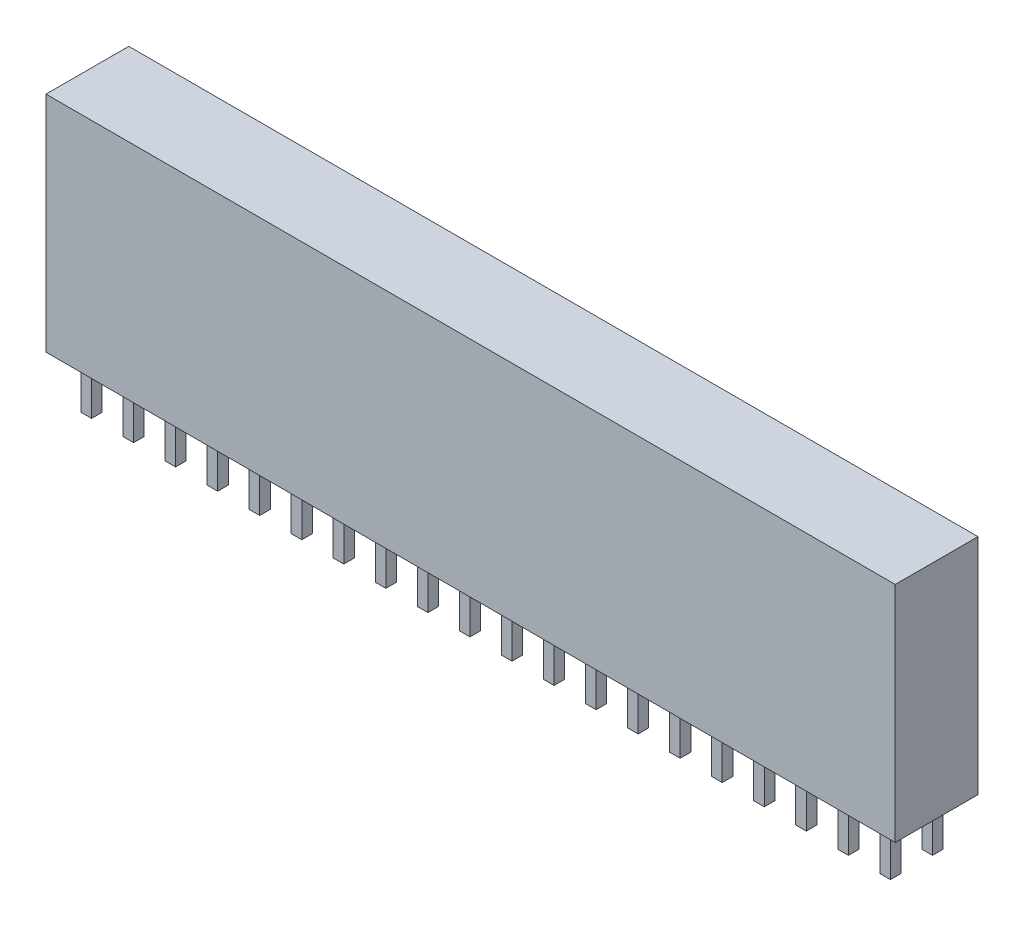
SolidWorks part; units mm, degrees
ref_plane "Front Plane" through (0, 0, 0) normal (0, 0, 1) x (1, 0, 0)
ref_plane "Top Plane" through (0, 0, 0) normal (0, 1, 0) x (1, 0, 0)
ref_plane "Right Plane" through (0, 0, 0) normal (1, 0, 0) x (0, 0, -1)
sketch "Sketch1" plane through (0, 0, 0) normal (0, 1, 0) x (1, 0, 0)
  line L1 (-25.65, -2.5) -> (25.65, -2.5)
  line L2 (-25.65, -2.5) -> (-25.65, 2.5)
  line L3 (-25.65, 2.5) -> (25.65, 2.5)
  line L4 (25.65, -2.5) -> (25.65, 2.5)
  line L5 (-25.65, -2.5) -> (25.65, 2.5) construction
  line L6 (-25.65, 2.5) -> (25.65, -2.5) construction
  point P0 (0, 0)
  dimension "D1" = 5
  dimension "D2" = 51.3
extrude "Boss-Extrude1" add sketch "Sketch1" along normal blind 13.5
sketch "Sketch2" plane through (0, 0, 0) normal (0, -1, 0) x (1, 0, 0)
  line L0 (-25.65, 0) -> (25.65, 0) construction
  line L1 (-25.65, -2.5) -> (-25.65, 2.5) construction
  line L2 (25.65, 2.5) -> (25.65, -2.5) construction
  line L3 (-25.65, 1.27) -> (25.65, 1.27) construction
  line L4 (-25.65, -1.27) -> (25.65, -1.27) construction
  line L5 (0, -2.5) -> (0, 2.5) construction
  line L6 (25.65, -2.5) -> (-25.65, -2.5) construction
  line L7 (-25.65, 2.5) -> (25.65, 2.5) construction
  line L8 (-21.91, 1.59) -> (-21.27, 1.59)
  line L9 (-24.45, 0.95) -> (-23.81, 0.95)
  line L10 (-24.45, 0.95) -> (-24.45, 1.59)
  line L11 (-24.45, 1.59) -> (-23.81, 1.59)
  line L12 (-23.81, 0.95) -> (-23.81, 1.59)
  line L13 (-24.45, 0.95) -> (-23.81, 1.59) construction
  line L14 (-24.45, 1.59) -> (-23.81, 0.95) construction
  line L15 (-21.91, 0.95) -> (-21.91, 1.59)
  line L16 (-21.91, 0.95) -> (-21.27, 0.95)
  line L17 (-21.27, 0.95) -> (-21.27, 1.59)
  line L18 (-19.37, 1.59) -> (-18.73, 1.59)
  line L19 (-19.37, 0.95) -> (-19.37, 1.59)
  line L20 (-19.37, 0.95) -> (-18.73, 0.95)
  line L21 (-18.73, 0.95) -> (-18.73, 1.59)
  line L22 (-16.83, 1.59) -> (-16.19, 1.59)
  line L23 (-16.83, 0.95) -> (-16.83, 1.59)
  line L24 (-16.83, 0.95) -> (-16.19, 0.95)
  line L25 (-16.19, 0.95) -> (-16.19, 1.59)
  line L26 (-14.29, 1.59) -> (-13.65, 1.59)
  line L27 (-14.29, 0.95) -> (-14.29, 1.59)
  line L28 (-14.29, 0.95) -> (-13.65, 0.95)
  line L29 (-13.65, 0.95) -> (-13.65, 1.59)
  line L30 (-11.75, 1.59) -> (-11.11, 1.59)
  line L31 (-11.75, 0.95) -> (-11.75, 1.59)
  line L32 (-11.75, 0.95) -> (-11.11, 0.95)
  line L33 (-11.11, 0.95) -> (-11.11, 1.59)
  line L34 (-9.21, 1.59) -> (-8.57, 1.59)
  line L35 (-9.21, 0.95) -> (-9.21, 1.59)
  line L36 (-9.21, 0.95) -> (-8.57, 0.95)
  line L37 (-8.57, 0.95) -> (-8.57, 1.59)
  line L38 (-6.67, 1.59) -> (-6.03, 1.59)
  line L39 (-6.67, 0.95) -> (-6.67, 1.59)
  line L40 (-6.67, 0.95) -> (-6.03, 0.95)
  line L41 (-6.03, 0.95) -> (-6.03, 1.59)
  line L42 (-4.13, 1.59) -> (-3.49, 1.59)
  line L43 (-4.13, 0.95) -> (-4.13, 1.59)
  line L44 (-4.13, 0.95) -> (-3.49, 0.95)
  line L45 (-3.49, 0.95) -> (-3.49, 1.59)
  line L46 (-1.59, 1.59) -> (-0.95, 1.59)
  line L47 (-1.59, 0.95) -> (-1.59, 1.59)
  line L48 (-1.59, 0.95) -> (-0.95, 0.95)
  line L49 (-0.95, 0.95) -> (-0.95, 1.59)
  line L50 (24.45, 0.95) -> (24.45, 1.59)
  line L51 (23.81, 0.95) -> (23.81, 1.59)
  line L52 (24.45, 1.59) -> (23.81, 1.59)
  line L53 (24.45, 0.95) -> (23.81, 0.95)
  line L54 (0.95, 0.95) -> (0.95, 1.59)
  line L55 (1.59, 0.95) -> (0.95, 0.95)
  line L56 (1.59, 0.95) -> (1.59, 1.59)
  line L57 (1.59, 1.59) -> (0.95, 1.59)
  line L58 (3.49, 0.95) -> (3.49, 1.59)
  line L59 (4.13, 0.95) -> (3.49, 0.95)
  line L60 (4.13, 0.95) -> (4.13, 1.59)
  line L61 (4.13, 1.59) -> (3.49, 1.59)
  line L62 (6.03, 0.95) -> (6.03, 1.59)
  line L63 (6.67, 0.95) -> (6.03, 0.95)
  line L64 (6.67, 0.95) -> (6.67, 1.59)
  line L65 (6.67, 1.59) -> (6.03, 1.59)
  line L66 (8.57, 0.95) -> (8.57, 1.59)
  line L67 (9.21, 0.95) -> (8.57, 0.95)
  line L68 (9.21, 0.95) -> (9.21, 1.59)
  line L69 (9.21, 1.59) -> (8.57, 1.59)
  line L70 (11.11, 0.95) -> (11.11, 1.59)
  line L71 (11.75, 0.95) -> (11.11, 0.95)
  line L72 (11.75, 0.95) -> (11.75, 1.59)
  line L73 (11.75, 1.59) -> (11.11, 1.59)
  line L74 (13.65, 0.95) -> (13.65, 1.59)
  line L75 (14.29, 0.95) -> (13.65, 0.95)
  line L76 (14.29, 0.95) -> (14.29, 1.59)
  line L77 (14.29, 1.59) -> (13.65, 1.59)
  line L78 (16.19, 0.95) -> (16.19, 1.59)
  line L79 (16.83, 0.95) -> (16.19, 0.95)
  line L80 (16.83, 0.95) -> (16.83, 1.59)
  line L81 (16.83, 1.59) -> (16.19, 1.59)
  line L82 (18.73, 0.95) -> (18.73, 1.59)
  line L83 (19.37, 0.95) -> (18.73, 0.95)
  line L84 (19.37, 0.95) -> (19.37, 1.59)
  line L85 (19.37, 1.59) -> (18.73, 1.59)
  line L86 (21.27, 0.95) -> (21.27, 1.59)
  line L87 (21.91, 0.95) -> (21.27, 0.95)
  line L88 (21.91, 0.95) -> (21.91, 1.59)
  line L89 (21.91, 1.59) -> (21.27, 1.59)
  line L90 (21.91, -1.59) -> (21.27, -1.59)
  line L91 (21.91, -0.95) -> (21.91, -1.59)
  line L92 (21.91, -0.95) -> (21.27, -0.95)
  line L93 (21.27, -0.95) -> (21.27, -1.59)
  line L94 (19.37, -1.59) -> (18.73, -1.59)
  line L95 (19.37, -0.95) -> (19.37, -1.59)
  line L96 (19.37, -0.95) -> (18.73, -0.95)
  line L97 (18.73, -0.95) -> (18.73, -1.59)
  line L98 (16.83, -1.59) -> (16.19, -1.59)
  line L99 (16.83, -0.95) -> (16.83, -1.59)
  line L100 (16.83, -0.95) -> (16.19, -0.95)
  line L101 (16.19, -0.95) -> (16.19, -1.59)
  line L102 (14.29, -1.59) -> (13.65, -1.59)
  line L103 (14.29, -0.95) -> (14.29, -1.59)
  line L104 (14.29, -0.95) -> (13.65, -0.95)
  line L105 (13.65, -0.95) -> (13.65, -1.59)
  line L106 (11.75, -1.59) -> (11.11, -1.59)
  line L107 (11.75, -0.95) -> (11.75, -1.59)
  line L108 (11.75, -0.95) -> (11.11, -0.95)
  line L109 (11.11, -0.95) -> (11.11, -1.59)
  line L110 (9.21, -1.59) -> (8.57, -1.59)
  line L111 (9.21, -0.95) -> (9.21, -1.59)
  line L112 (9.21, -0.95) -> (8.57, -0.95)
  line L113 (8.57, -0.95) -> (8.57, -1.59)
  line L114 (6.67, -1.59) -> (6.03, -1.59)
  line L115 (6.67, -0.95) -> (6.67, -1.59)
  line L116 (6.67, -0.95) -> (6.03, -0.95)
  line L117 (6.03, -0.95) -> (6.03, -1.59)
  line L118 (4.13, -1.59) -> (3.49, -1.59)
  line L119 (4.13, -0.95) -> (4.13, -1.59)
  line L120 (4.13, -0.95) -> (3.49, -0.95)
  line L121 (3.49, -0.95) -> (3.49, -1.59)
  line L122 (1.59, -1.59) -> (0.95, -1.59)
  line L123 (1.59, -0.95) -> (1.59, -1.59)
  line L124 (1.59, -0.95) -> (0.95, -0.95)
  line L125 (0.95, -0.95) -> (0.95, -1.59)
  line L126 (24.45, -0.95) -> (23.81, -0.95)
  line L127 (24.45, -1.59) -> (23.81, -1.59)
  line L128 (23.81, -0.95) -> (23.81, -1.59)
  line L129 (24.45, -0.95) -> (24.45, -1.59)
  line L130 (-0.95, -0.95) -> (-0.95, -1.59)
  line L131 (-1.59, -0.95) -> (-0.95, -0.95)
  line L132 (-1.59, -0.95) -> (-1.59, -1.59)
  line L133 (-1.59, -1.59) -> (-0.95, -1.59)
  line L134 (-3.49, -0.95) -> (-3.49, -1.59)
  line L135 (-4.13, -0.95) -> (-3.49, -0.95)
  line L136 (-4.13, -0.95) -> (-4.13, -1.59)
  line L137 (-4.13, -1.59) -> (-3.49, -1.59)
  line L138 (-6.03, -0.95) -> (-6.03, -1.59)
  line L139 (-6.67, -0.95) -> (-6.03, -0.95)
  line L140 (-6.67, -0.95) -> (-6.67, -1.59)
  line L141 (-6.67, -1.59) -> (-6.03, -1.59)
  line L142 (-8.57, -0.95) -> (-8.57, -1.59)
  line L143 (-9.21, -0.95) -> (-8.57, -0.95)
  line L144 (-9.21, -0.95) -> (-9.21, -1.59)
  line L145 (-9.21, -1.59) -> (-8.57, -1.59)
  line L146 (-11.11, -0.95) -> (-11.11, -1.59)
  line L147 (-11.75, -0.95) -> (-11.11, -0.95)
  line L148 (-11.75, -0.95) -> (-11.75, -1.59)
  line L149 (-11.75, -1.59) -> (-11.11, -1.59)
  line L150 (-13.65, -0.95) -> (-13.65, -1.59)
  line L151 (-14.29, -0.95) -> (-13.65, -0.95)
  line L152 (-14.29, -0.95) -> (-14.29, -1.59)
  line L153 (-14.29, -1.59) -> (-13.65, -1.59)
  line L154 (-16.19, -0.95) -> (-16.19, -1.59)
  line L155 (-16.83, -0.95) -> (-16.19, -0.95)
  line L156 (-16.83, -0.95) -> (-16.83, -1.59)
  line L157 (-16.83, -1.59) -> (-16.19, -1.59)
  line L158 (-18.73, -0.95) -> (-18.73, -1.59)
  line L159 (-19.37, -0.95) -> (-18.73, -0.95)
  line L160 (-19.37, -0.95) -> (-19.37, -1.59)
  line L161 (-19.37, -1.59) -> (-18.73, -1.59)
  line L162 (-21.27, -0.95) -> (-21.27, -1.59)
  line L163 (-21.91, -0.95) -> (-21.27, -0.95)
  line L164 (-21.91, -0.95) -> (-21.91, -1.59)
  line L165 (-23.81, -0.95) -> (-23.81, -1.59)
  line L166 (-24.45, -1.59) -> (-23.81, -1.59)
  line L167 (-24.45, -0.95) -> (-24.45, -1.59)
  line L168 (-24.45, -0.95) -> (-23.81, -0.95)
  line L169 (-21.91, -1.59) -> (-21.27, -1.59)
  point P16 (-24.13, 1.27)
  point P97 (-1.27, 1.59)
  point P98 (1.27, 1.59)
  point P99 (-24.13, 1.59)
  point P100 (-21.59, 1.59)
  dimension "D1" = 2.54
  dimension "D2" = 0.64
  dimension "D3" = 10
  dimension "D4" = 2.54
  dimension "D5" = 2.54
extrude "Boss-Extrude2" add sketch "Sketch2" along normal blind 3
